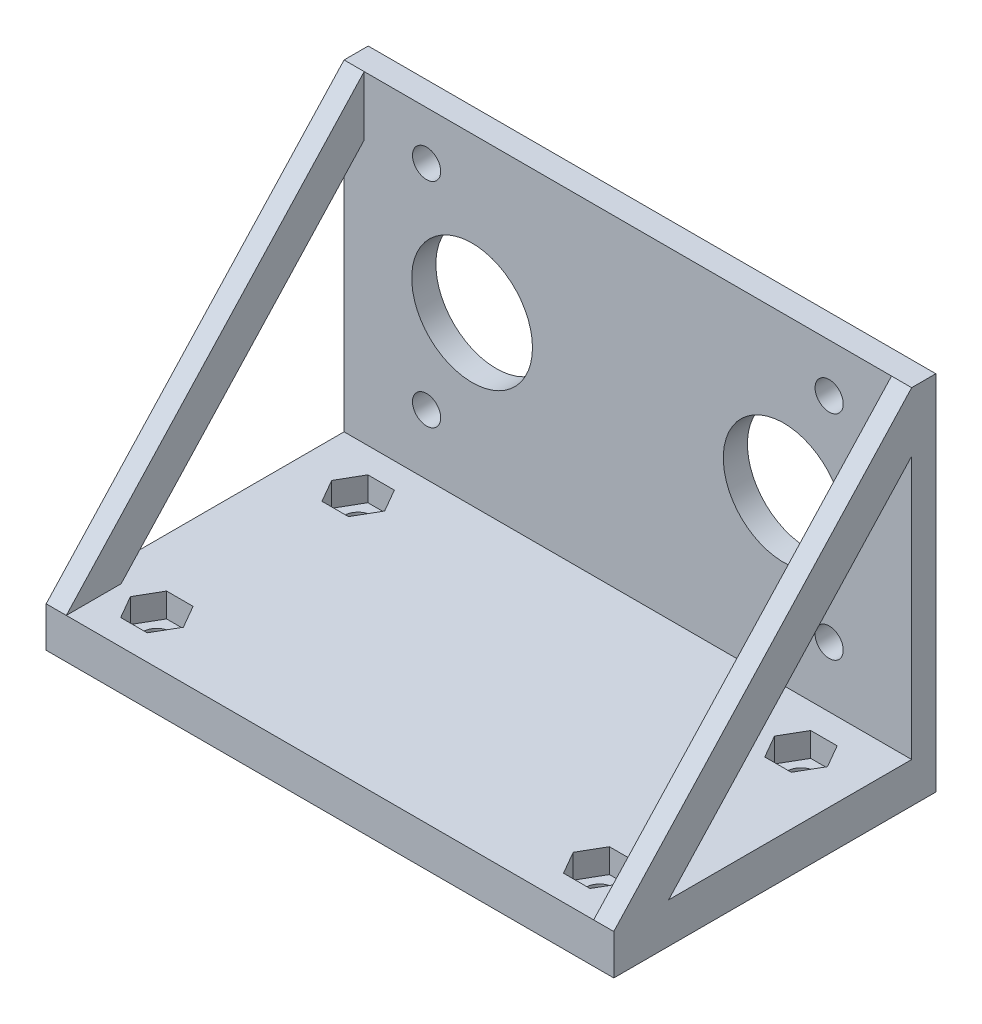
SolidWorks part; units mm, degrees
ref_plane "前视基准面" through (0, 0, 0) normal (0, 0, 1) x (1, 0, 0)
ref_plane "上视基准面" through (0, 0, 0) normal (0, 1, 0) x (1, 0, 0)
ref_plane "右视基准面" through (0, 0, 0) normal (1, 0, 0) x (0, 0, -1)
sketch "草图1" plane through (0, 0, 0) normal (0, 0, 1) x (1, 0, 0)
  line L1 (0, 0) -> (64.5, 0)
  line L2 (0, 0) -> (0, 45)
  line L3 (0, 45) -> (64.5, 45)
  line L4 (64.5, 0) -> (64.5, 45)
  dimension "D1" = 64.5
  dimension "D2" = 45
extrude "凸台-拉伸1" add sketch "草图1" along normal blind 3
sketch "草图2" plane through (0, 0, 3) normal (0, 0, 1) x (1, 0, 0)
  line L0 (32.25, 45) -> (32.25, 25.75)
  line L1 (64.5, 45) -> (0, 45) construction
  line L3 (7.25, 12.5) -> (57.25, 12.5)
  line L4 (7.25, 12.5) -> (7.25, 39)
  line L5 (7.25, 39) -> (57.25, 39)
  line L6 (57.25, 12.5) -> (57.25, 39)
  line L7 (7.25, 12.5) -> (57.25, 39) construction
  line L8 (7.25, 39) -> (57.25, 12.5) construction
  line L9 (7.25, 25.75) -> (0, 25.75)
  line L10 (0, 45) -> (0, 0) construction
  line L11 (0, 25.75) -> (12.9, 25.75)
  line L12 (57.25, 25.75) -> (64.5, 25.75)
  line L13 (64.5, 0) -> (64.5, 45) construction
  line L14 (64.5, 25.75) -> (51.6, 25.75)
  dimension "D1" = 26.5
  dimension "D2" = 50
  dimension "D3" = 6
  dimension "D4" = 12.9
  dimension "D5" = 12.9
sketch "草图3" plane through (0, 0, 3) normal (0, 0, 1) x (1, 0, 0)
  point P0 (7.25, 39)
  point P3 (57.25, 39)
  point P6 (57.25, 12.5)
  point P9 (7.25, 12.5)
hole_wizard "孔1" positions "草图3" profile "草图4" legacy end condition through all
sketch "草图4" plane through (7.25, 39, 3) normal (1, 0, 0) x (0, -1, 0)
  line L0 (0, 0) -> (0, 3)
  line L1 (0, 3) -> (1.75, 3)
  line L2 (1.75, 3) -> (1.75, 0)
  line L3 (1.75, 0) -> (0, 0)
  line L4 (0, 110) -> (0, -10) construction
  dimension "直径" = 3.5
  dimension "深度" = 3
sketch "草图5" plane through (0, 0, 3) normal (0, 0, 1) x (1, 0, 0)
  point P0 (12.9, 25.75)
  point P3 (51.6, 25.75)
hole_wizard "孔2" positions "草图5" profile "草图6" legacy end condition through all
sketch "草图6" plane through (12.9, 25.75, 3) normal (1, 0, 0) x (0, -1, 0)
  line L0 (0, 0) -> (0, 3)
  line L1 (0, 3) -> (7.5, 3)
  line L2 (7.5, 3) -> (7.5, 0)
  line L3 (7.5, 0) -> (0, 0)
  line L4 (0, 110) -> (0, -10) construction
  dimension "直径" = 15
  dimension "深度" = 3
sketch "草图7" plane through (0, 0, 3) normal (0, 0, 1) x (1, 0, 0)
  line L0 (64.5, 0) -> (64.5, 45) construction
  line L1 (0, 0) -> (64.5, 0)
  line L2 (0, 0) -> (0, 5)
  line L3 (0, 5) -> (64.5, 5)
  line L4 (64.5, 0) -> (64.5, 5)
  dimension "D1" = 5
extrude "凸台-拉伸2" add sketch "草图7" along normal blind 37 contours L2 L1 L4 L3
sketch "草图8" plane through (0, 0, 0) normal (0, -1, 0) x (1, 0, 0)
  line L0 (0, 40) -> (64.5, 3)
  line L1 (0, 40) -> (64.5, 40)
  line L2 (0, 40) -> (0, 3)
  line L3 (0, 3) -> (64.5, 3)
  line L4 (64.5, 40) -> (64.5, 3)
  line L6 (4.75, 9) -> (59.75, 9)
  line L7 (4.75, 9) -> (4.75, 34)
  line L8 (4.75, 34) -> (59.75, 34)
  line L9 (59.75, 9) -> (59.75, 34)
  line L10 (4.75, 9) -> (59.75, 34) construction
  line L11 (4.75, 34) -> (59.75, 9) construction
  point P6 (32.25, 21.5)
  dimension "D1" = 55
  dimension "D2" = 25
sketch "草图9" plane through (0, 0, 0) normal (0, -1, 0) x (-1, 0, 0)
  point P0 (-4.75, -34)
  point P3 (-4.75, -9)
  point P6 (-59.75, -9)
  point P9 (-59.75, -34)
hole_wizard "孔3" positions "草图9" profile "草图10" legacy end condition through all
sketch "草图10" plane through (4.75, 0, 34) normal (1, 0, 0) x (0, 0, -1)
  line L0 (0, 0) -> (0, 45)
  line L1 (0, 45) -> (1.75, 45)
  line L2 (1.75, 45) -> (1.75, 0)
  line L3 (1.75, 0) -> (0, 0)
  line L4 (0, 110) -> (0, -10) construction
  dimension "直径" = 3.5
  dimension "深度" = 45
sketch "草图11" plane through (0, 5, 0) normal (0, 1, 0) x (1, 0, 0)
  line L1 (63.0409, -9) -> (61.3954, -6.15)
  line L2 (61.3954, -6.15) -> (58.1046, -6.15)
  line L3 (58.1046, -6.15) -> (56.4591, -9)
  line L4 (56.4591, -9) -> (58.1046, -11.85)
  line L5 (58.1046, -11.85) -> (61.3954, -11.85)
  line L6 (61.3954, -11.85) -> (63.0409, -9)
  line L7 (63.0409, -34) -> (61.3954, -31.15)
  line L8 (61.3954, -31.15) -> (58.1046, -31.15)
  line L9 (58.1046, -31.15) -> (56.4591, -34)
  line L10 (56.4591, -34) -> (58.1046, -36.85)
  line L11 (58.1046, -36.85) -> (61.3954, -36.85)
  line L12 (61.3954, -36.85) -> (63.0409, -34)
  line L13 (8.0409, -34) -> (6.3954, -31.15)
  line L14 (6.3954, -31.15) -> (3.1046, -31.15)
  line L15 (3.1046, -31.15) -> (1.4591, -34)
  line L16 (1.4591, -34) -> (3.1046, -36.85)
  line L17 (3.1046, -36.85) -> (6.3954, -36.85)
  line L18 (6.3954, -36.85) -> (8.0409, -34)
  line L19 (8.0409, -9) -> (6.3954, -6.15)
  line L20 (6.3954, -6.15) -> (3.1046, -6.15)
  line L21 (3.1046, -6.15) -> (1.4591, -9)
  line L22 (1.4591, -9) -> (3.1046, -11.85)
  line L23 (3.1046, -11.85) -> (6.3954, -11.85)
  line L24 (6.3954, -11.85) -> (8.0409, -9)
  circle A0 centre (59.75, -9) radius 2.85 construction
  circle A1 centre (59.75, -34) radius 2.85 construction
  circle A2 centre (4.75, -34) radius 2.85 construction
  circle A3 centre (4.75, -9) radius 2.85 construction
  point P28 (59.75, -36.85)
  dimension "D1" = 5.7
  dimension "D2" = 5.7
  dimension "D3" = 5.7
  dimension "D4" = 5.7
extrude "切除-拉伸1" cut sketch "草图11" against normal blind 3
ref_plane "基准面1" through (32.25, 0, 0) normal (-1, 0, 0) x (0, 0, 1)
sketch "草图14" plane through (0, 0, 0) normal (-1, 0, 0) x (0, 0, 1)
  line L0 (0, 45) -> (0, 0)
  line L1 (0, 0) -> (40, 0)
  line L2 (40, 0) -> (40, 5)
  line L3 (40, 5) -> (3, 5)
  line L4 (3, 5) -> (3, 45)
  line L5 (3, 45) -> (0, 45)
  line L6 (3, 45) -> (40, 5)
  line L7 (3, 37.6367) -> (33.1889, 5)
  line L8 (3, 37.6367) -> (3, 45)
  line L9 (33.1889, 5) -> (40, 5)
  line M9 (0, 45) -> (0, 0)
  line M10 (0, 0) -> (40, 0)
  line M11 (40, 0) -> (40, 5)
  line M12 (40, 5) -> (3, 5)
  line M13 (3, 5) -> (3, 45)
  line M14 (3, 45) -> (0, 45)
  dimension "D1" = 5
extrude "凸台-拉伸3" add sketch "草图14" along normal blind 3 contours L3 L4 M14 M9 M10 M11 M12 M13 | L4 L7 L6 M12
mirror "镜向1" about plane through (32.25, 0, 0) normal (-1, 0, 0) of "凸台-拉伸3"
sketch "草图15" plane through (0, 5, 0) normal (0, 1, 0) x (1, 0, 0)
  line L0 (-3, -3) -> (0, -3) construction
  line L1 (-0.5, -3) -> (65, -3)
  line L2 (-0.5, -3) -> (-0.5, -40)
  line L3 (-0.5, -40) -> (65, -40)
  line L4 (65, -3) -> (65, -40)
  line L5 (67.5, -40) -> (64.5, -40) construction
  line L6 (0, -40) -> (0, -3) construction
  line L7 (64.5, -40) -> (64.5, -3) construction
  dimension "D1" = 0.5
  dimension "D2" = 0.5
extrude "切除-拉伸2" cut sketch "草图15" along normal blind 40
